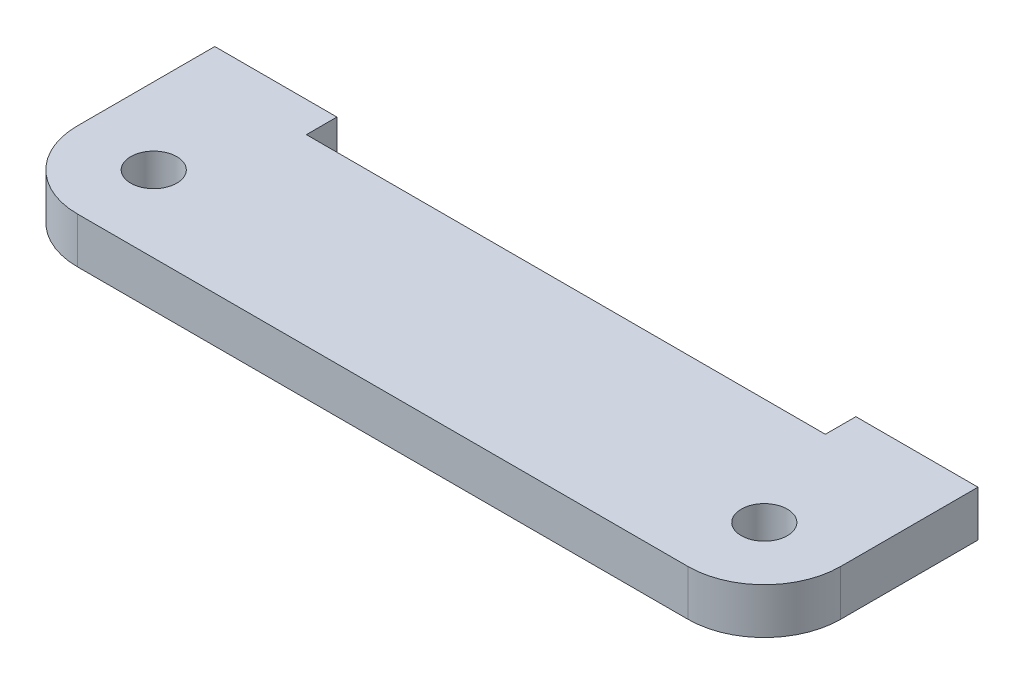
SolidWorks part; units mm, degrees
ref_plane "Front Plane" through (0, 0, 0) normal (0, 0, 1) x (1, 0, 0)
ref_plane "Top Plane" through (0, 0, 0) normal (0, 1, 0) x (1, 0, 0)
ref_plane "Right Plane" through (0, 0, 0) normal (1, 0, 0) x (0, 0, -1)
sketch "Sketch1" plane through (0, 0, 0) normal (0, 1, 0) x (1, 0, 0)
  line L1 (-17, 12) -> (17, 12)
  line L2 (-25, 14) -> (-25, 0)
  line L3 (-25, 0) -> (25, 0)
  line L4 (25, 14) -> (25, 0)
  line L5 (-25, 14) -> (-17, 14)
  line L6 (-17, 14) -> (-17, 12)
  line L7 (17, 12) -> (17, 14)
  line L8 (17, 14) -> (25, 14)
  dimension "D1" = 50
  dimension "D2" = 12
  dimension "D3" = 8
  dimension "D4" = 2
extrude "Boss-Extrude1" add sketch "Sketch1" along normal blind 3
hole_wizard "M3 Clearance Hole1" positions "Sketch3" profile "Sketch4" hole size "M3" standard "ANSI Metric" end condition through all
sketch "Sketch3" plane through (0, 3, 0) normal (0, 1, 0) x (1, 0, 0)
  line L0 (-20, 5) -> (20, 5) construction
  line L2 (0, 0) -> (0, 5) construction
  line L3 (-25, 0) -> (25, 0) construction
  point P0 (20, 5)
  point P2 (-20, 5)
  dimension "D1" = 40
  dimension "D2" = 5
sketch "Sketch4" plane through (20, 3, -5) normal (1, 0, 0) x (0, 0, 1)
  line L0 (0, 0) -> (0, 3)
  line L1 (0, 3) -> (1.51, 3)
  line L2 (1.51, 3) -> (1.51, 0)
  line L5 (1.51, 0) -> (0, 0)
  line L11 (0, -6.35) -> (0, 107.95) construction
  dimension "Thru Hole Dia." = 3.02
  dimension "Thru Hole Depth" = 3
fillet "Fillet1" radius 5 2 edges at (-25, 1.5, 0) (25, 1.5, 0)
